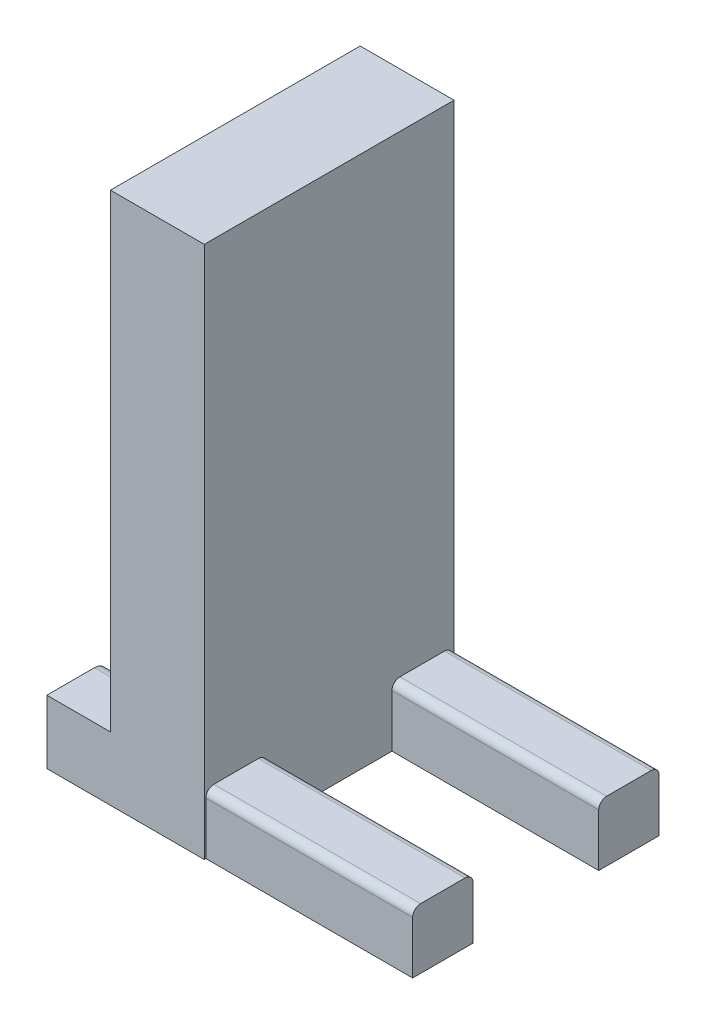
SolidWorks part; units mm, degrees
material "ABS"
ref_plane "正面" through (0, 0, 0) normal (0, 0, 1) x (1, 0, 0)
ref_plane "平面" through (0, 0, 0) normal (0, 1, 0) x (1, 0, 0)
ref_plane "右側面" through (0, 0, 0) normal (1, 0, 0) x (0, 0, -1)
sketch "ｽｹｯﾁ2" plane through (0, 0, 0) normal (0, 1, 0) x (1, 0, 0)
  line L1 (2.95, -7.85) -> (-2.95, -7.85)
  line L2 (2.95, -7.85) -> (2.95, 7.85)
  line L3 (2.95, 7.85) -> (-2.95, 7.85)
  line L4 (-2.95, -7.85) -> (-2.95, 7.85)
  line L5 (2.95, -7.85) -> (-2.95, 7.85) construction
  line L6 (2.95, 7.85) -> (-2.95, -7.85) construction
  point P0 (0, 0)
  dimension "D1" = 5.9
  dimension "D2" = 15.7
extrude "ﾎﾞｽ - 押し出し1" add sketch "ｽｹｯﾁ2" along normal blind 33.5
sketch "ｽｹｯﾁ3" plane through (0, 0, 0) normal (0, -1, 0) x (1, 0, 0)
  circle A0 centre (0, 0) radius 0.975
  dimension "D1" = 1.95
extrude "ｶｯﾄ - 押し出し1" cut sketch "ｽｹｯﾁ3" against normal blind 10
sketch "ｽｹｯﾁ4" plane through (2.95, 0, 0) normal (1, 0, 0) x (0, 0, -1)
  line L0 (-5.85, 33.5) -> (-5.85, 0) construction
  line L5 (-7.85, 33.5) -> (7.85, 33.5) construction
  line L6 (-7.85, 0) -> (7.85, 0) construction
  line L12 (5.85, 33.5) -> (5.85, 0) construction
  line L13 (-7.85, 33.5) -> (-7.85, 0) construction
  line L14 (7.85, 33.5) -> (7.85, 0) construction
  line L16 (-3.95, 3.8) -> (-7.75, 3.8)
  line L17 (-3.95, 3.8) -> (-3.95, 0)
  line L18 (-3.95, 0) -> (-7.75, 0)
  line L19 (-7.75, 3.8) -> (-7.75, 0)
  line L20 (-3.95, 3.8) -> (-7.75, 0) construction
  line L21 (-3.95, 0) -> (-7.75, 3.8) construction
  line L22 (7.75, 3.8) -> (3.95, 3.8)
  line L23 (7.75, 3.8) -> (7.75, 0)
  line L24 (7.75, 0) -> (3.95, 0)
  line L25 (3.95, 3.8) -> (3.95, 0)
  line L26 (7.75, 3.8) -> (3.95, 0) construction
  line L27 (7.75, 0) -> (3.95, 3.8) construction
  point P13 (-5.85, 1.9)
  point P18 (5.85, 1.9)
  dimension "D1" = 2
  dimension "D2" = 2
  dimension "D3" = 3.8
  dimension "D4" = 3.8
extrude "ﾎﾞｽ - 押し出し2" add sketch "ｽｹｯﾁ4" along normal blind 13
sketch "ｽｹｯﾁ5" plane through (-2.95, 0, 0) normal (-1, 0, 0) x (0, 0, 1)
  line L1 (-7.85, 4) -> (-4.05, 4)
  line L2 (-7.85, 4) -> (-7.85, 0)
  line L3 (-7.85, 0) -> (-4.05, 0)
  line L4 (-4.05, 4) -> (-4.05, 0)
  line L5 (-7.85, 4) -> (-4.05, 0) construction
  line L6 (-7.85, 0) -> (-4.05, 4) construction
  line L7 (4.05, 4) -> (7.85, 4)
  line L8 (4.05, 4) -> (4.05, 0)
  line L9 (4.05, 0) -> (7.85, 0)
  line L10 (7.85, 4) -> (7.85, 0)
  line L11 (4.05, 4) -> (7.85, 0) construction
  line L12 (4.05, 0) -> (7.85, 4) construction
  point P0 (-5.95, 2)
  point P6 (5.95, 2)
  dimension "D1" = 4
  dimension "D2" = 3.8
extrude "ﾎﾞｽ - 押し出し3" add sketch "ｽｹｯﾁ5" along normal blind 4
fillet "ﾌｨﾚｯﾄ1" radius 0.8 2 edges at (-4.95, 4, 4.05) (-4.95, 4, -4.05)
fillet "ﾌｨﾚｯﾄ2" radius 0.5 4 edges at (9.45, 3.8, 7.75) (9.45, 3.8, 3.95) (9.45, 3.8, -3.95) (9.45, 3.8, -7.75)
